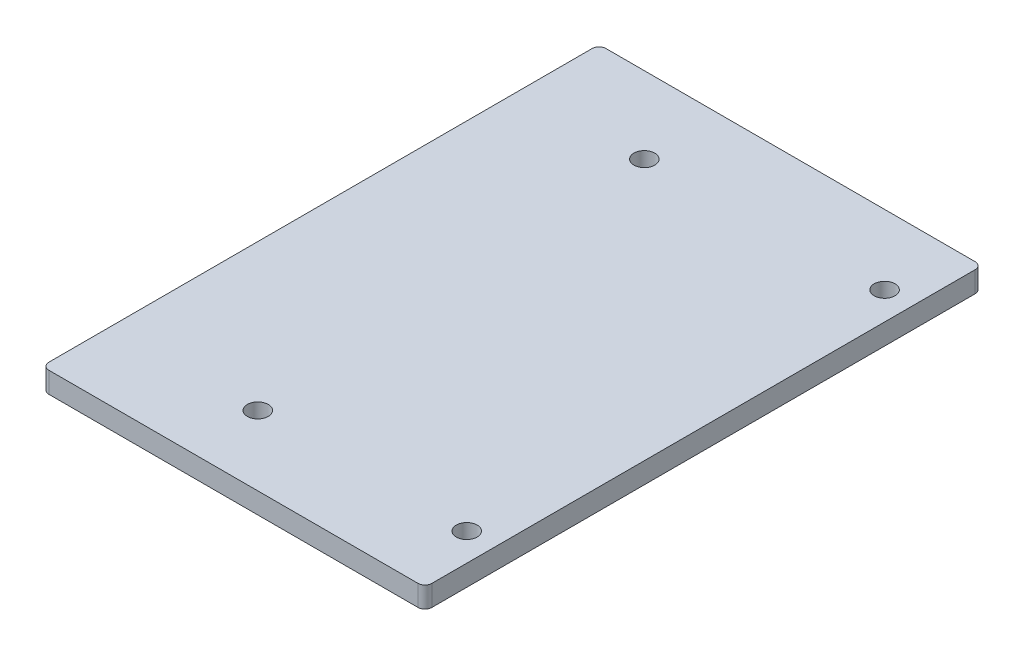
SolidWorks part; units mm, degrees
material "A-玻璃纤维"
ref_plane "前视基准面" through (0, 0, 0) normal (0, 0, 1) x (1, 0, 0)
ref_plane "上视基准面" through (0, 0, 0) normal (0, 1, 0) x (1, 0, 0)
ref_plane "右视基准面" through (0, 0, 0) normal (1, 0, 0) x (0, 0, -1)
other "Configuration Table"
sketch "草图1" plane through (0, 0, 0) normal (0, 1, 0) x (1, 0, 0)
  line L0 (0, 0) -> (32.1044, 0) construction
  line L5 (0, 0) -> (0, -29.04) construction
  line L7 (0, 0) -> (55, 0)
  line L8 (0, 0) -> (0, -80)
  line L9 (0, -80) -> (55, -80)
  line L10 (55, 0) -> (55, -80)
  circle A0 centre (17.5, -11) radius 1.5
  circle A1 centre (51, -10) radius 1.5
  circle A2 centre (21, -70) radius 1.5
  circle A3 centre (51, -70) radius 1.5
  dimension "D3" = 3
  dimension "D4" = 3
  dimension "D5" = 3
  dimension "D6" = 3
  dimension "D1" = 55
  dimension "D2" = 80
  dimension "D7" = 17.5
  dimension "D8" = 11
  dimension "D9" = 10
  dimension "D10" = 51
  dimension "D11" = 21
  dimension "D12" = 70
  dimension "D13" = 70
  dimension "D14" = 51
extrude "凸台-拉伸1" add sketch "草图1" along normal blind 3
fillet "圆角1" radius 1 4 edges at (55, 1.5, 0) (0, 1.5, 0) (0, 1.5, 80) (55, 1.5, 80)
